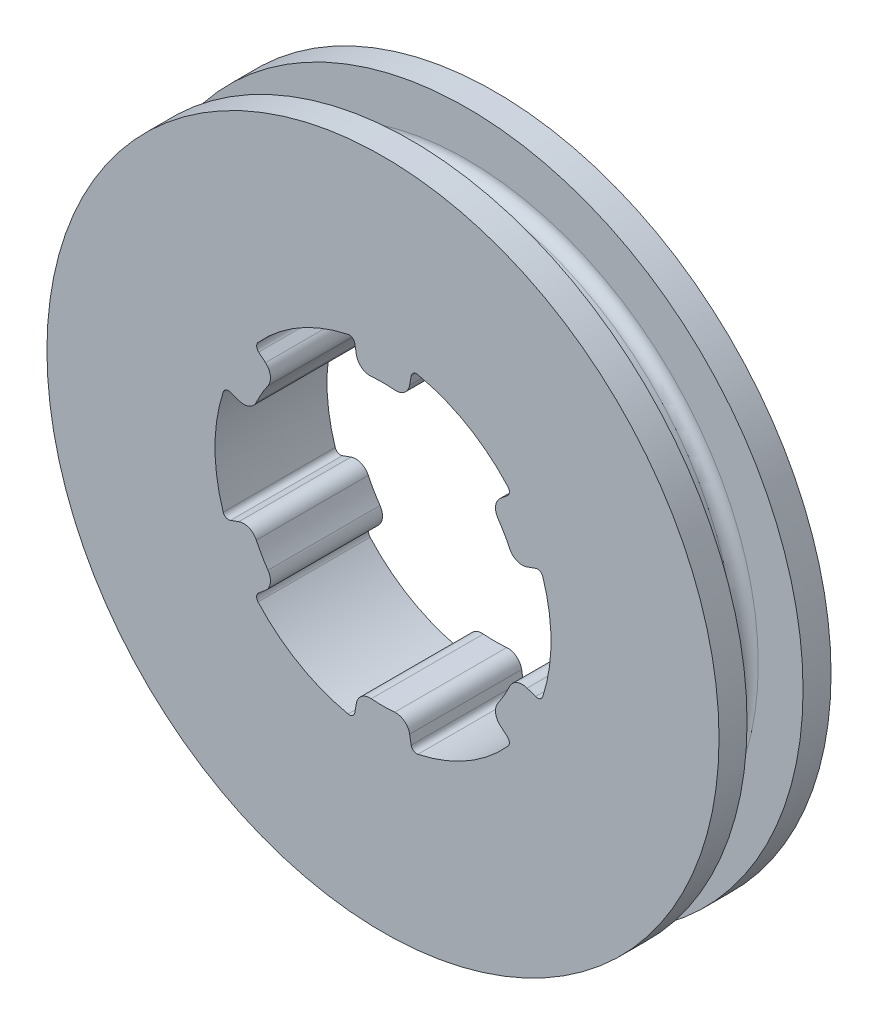
SolidWorks part; units mm, degrees
ref_plane "Front Plane" through (0, 0, 0) normal (0, 0, 1) x (1, 0, 0)
ref_plane "Top Plane" through (0, 0, 0) normal (0, 1, 0) x (1, 0, 0)
ref_plane "Right Plane" through (0, 0, 0) normal (1, 0, 0) x (0, 0, -1)
sketch "Sketch1" plane through (0, 0, 0) normal (0, 0, 1) x (1, 0, 0)
  circle A0 centre (0, 0) radius 30
  circle A1 centre (0, 0) radius 60
  dimension "D1" = 120
  dimension "D2" = 60
extrude "Boss-Extrude1" add sketch "Sketch1" along normal mid plane 20
sketch "Sketch2" plane through (0, 0, 0) normal (1, 0, 0) x (0, 0, -1)
  line L0 (0, -1000) -> (0, 49000) construction
  line L1 (10, 60) -> (-10, 60) construction
  line L2 (-5, 50) -> (5, 50)
  line L3 (-5, 50) -> (-5, 70)
  line L4 (-5, 70) -> (5, 70)
  line L5 (5, 50) -> (5, 70)
  line L6 (-5, 50) -> (5, 70) construction
  line L7 (-5, 70) -> (5, 50) construction
  line L8 (-1000, 0) -> (49000, 0) construction
  point P1 (0, 60)
  dimension "D1" = 10
  dimension "D2" = 20
revolve "Cut-Revolve1" cut sketch "Sketch2" angle 360 about L8
sketch "Sketch3" plane through (0, 0, 10) normal (0, 0, 1) x (1, 0, 0)
  line L0 (0, -1000) -> (0, 49000) construction
  line L1 (5.2094, 29.5442) -> (4.3412, 24.6202)
  line L2 (-5.2094, 29.5442) -> (-4.3412, 24.6202)
  arc A0 (4.3412, 24.6202) -> (-4.3412, 24.6202) centre (0, 0) ccw
  arc A1 (5.2094, 29.5442) -> (-5.2094, 29.5442) centre (0, 0) ccw
  dimension "D1" = 50
  dimension "D2" = 60
  dimension "D3" = 20
extrude "Boss-Extrude2" add sketch "Sketch3" against normal blind 20
fillet "Fillet1" radius 2.5 2 edges at (4.3412, 24.6202, 0) (-4.3412, 24.6202, 0)
fillet "Fillet2" radius 1 2 edges at (-5.2094, 29.5442, 0) (5.2094, 29.5442, 0)
pattern_circular "CirPattern1" count 6 every 60 about axis through (0, 0, 0) along (0, 0, 1) of "Boss-Extrude2", "Fillet2", "Fillet1"
fillet "Fillet3" radius 2 2 edges at (50, 0, 5) (50, 0, -5)
